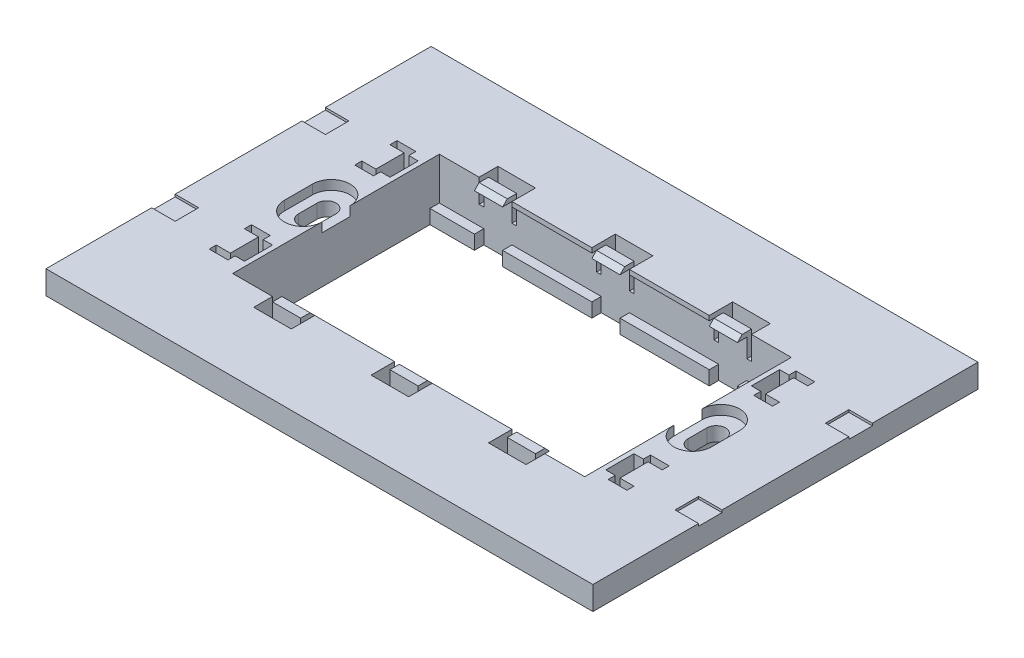
SolidWorks part; units mm, degrees
material "ABS"
ref_plane "Alzado" through (0, 0, 0) normal (0, 0, 1) x (1, 0, 0)
ref_plane "Planta" through (0, 0, 0) normal (0, 1, 0) x (1, 0, 0)
ref_plane "Vista lateral" through (0, 0, 0) normal (1, 0, 0) x (0, 0, -1)
sketch "Croquis1" plane through (0, 0, 0) normal (0, 1, 0) x (1, 0, 0)
  line L1 (-58.225, 41) -> (58.225, 41)
  line L2 (-58.225, 41) -> (-58.225, -41)
  line L3 (-58.225, -41) -> (58.225, -41)
  line L4 (58.225, 41) -> (58.225, -41)
  line L5 (-58.225, 41) -> (58.225, -41) construction
  line L6 (-58.225, -41) -> (58.225, 41) construction
  point P0 (0, 0)
  dimension "D1" = 82
  dimension "D2" = 116.45
extrude "Saliente-Extruir2" add sketch "Croquis1" along normal blind 5
sketch "Croquis2" plane through (0, 5, 0) normal (0, 1, 0) x (1, 0, 0)
  line L1 (-37.475, -22) -> (37.475, -22)
  line L2 (-37.475, -22) -> (-37.475, 22)
  line L3 (-37.475, 22) -> (37.475, 22)
  line L4 (37.475, -22) -> (37.475, 22)
  line L5 (-37.475, -22) -> (37.475, 22) construction
  line L6 (-37.475, 22) -> (37.475, -22) construction
  point P0 (0, 0)
  dimension "D1" = 74.95
  dimension "D2" = 44
extrude "Cortar-Extruir1" cut sketch "Croquis2" against normal blind 5
sketch "Croquis3" plane through (0, 0, 0) normal (0, -1, 0) x (1, 0, 0)
  line L1 (37.475, 22) -> (-37.475, 22)
  line L2 (37.475, 22) -> (37.475, -22)
  line L3 (37.475, -22) -> (-37.475, -22)
  line L4 (-37.475, 22) -> (-37.475, -22)
  line L5 (37.475, 22) -> (-37.475, -22) construction
  line L6 (37.475, -22) -> (-37.475, 22) construction
  line L7 (-38.475, 23) -> (38.475, 23)
  line L8 (-38.475, 23) -> (-38.475, -23)
  line L9 (-38.475, -23) -> (38.475, -23)
  line L10 (38.475, 23) -> (38.475, -23)
  line L11 (-38.475, 23) -> (38.475, -23) construction
  line L12 (-38.475, -23) -> (38.475, 23) construction
  point P0 (0, 0)
  point P7 (0, 0)
  dimension "D1" = 1
  dimension "D2" = 1
extrude "Saliente-Extruir3" add sketch "Croquis3" along normal blind 7
sketch "Croquis4" plane through (0, -7, 0) normal (0, -1, 0) x (1, 0, 0)
  line L0 (37.475, -22) -> (37.475, 22) construction
  line L1 (-37.475, 22) -> (37.475, 22)
  line L2 (-37.475, 22) -> (-37.475, 19)
  line L3 (-37.475, 19) -> (37.475, 19)
  line L4 (37.475, 22) -> (37.475, 19)
  line L5 (0, 0) -> (-23.0927, 0)
  line L6 (37.475, -22) -> (37.475, -19)
  line L7 (-37.475, -19) -> (37.475, -19)
  line L8 (-37.475, -22) -> (-37.475, -19)
  line L9 (-37.475, -22) -> (37.475, -22)
  line M5 (37.475, -22) -> (-37.475, -22)
  line M6 (-37.475, -22) -> (-37.475, 22)
  line M7 (-37.475, 22) -> (37.475, 22)
  line M8 (37.475, 22) -> (37.475, -22)
  dimension "D1" = 3
extrude "Saliente-Extruir4" add sketch "Croquis4" against normal blind 3 contours L3 M6 M8 M7 | L7 M6 M5 M8
sketch "Croquis5" plane through (0, -7, 0) normal (0, -1, 0) x (1, 0, 0)
  line L0 (0, -19) -> (0, -21)
  line L1 (-37.475, -19) -> (37.475, -19) construction
  line L2 (-3, -19) -> (-3, -21)
  line L3 (3, -19) -> (3, -21)
  line L4 (-3, -21) -> (3, -21)
  line L5 (-3, -19) -> (3, -19)
  line L6 (-25, -19) -> (-25, -13.1043)
  line L7 (-28, -19) -> (-28, -21)
  line L8 (-28, -21) -> (-22, -21)
  line L9 (-22, -21) -> (-22, -19)
  line L10 (-22, -19) -> (-28, -19)
  line L11 (0, 0) -> (-20.2994, 0)
  line L12 (-3, 19) -> (3, 19)
  line L13 (-3, 21) -> (3, 21)
  line L14 (3, 19) -> (3, 21)
  line L15 (-3, 19) -> (-3, 21)
  line L16 (0, 19) -> (0, 21)
  line L17 (-22, 19) -> (-28, 19)
  line L18 (-22, 21) -> (-22, 19)
  line L19 (-28, 21) -> (-22, 21)
  line L20 (-28, 19) -> (-28, 21)
  line L21 (-25, 19) -> (-25, 13.1043)
  line L22 (25, 19) -> (25, 13.1043)
  line L23 (28, 19) -> (28, 21)
  line L24 (28, 21) -> (22, 21)
  line L25 (22, 21) -> (22, 19)
  line L26 (22, 19) -> (28, 19)
  line L27 (22, -19) -> (28, -19)
  line L28 (22, -21) -> (22, -19)
  line L29 (28, -21) -> (22, -21)
  line L30 (28, -19) -> (28, -21)
  line L31 (25, -19) -> (25, -13.1043)
  line M2 (37.475, -19) -> (-37.475, -19)
  line M4 (-37.475, 19) -> (37.475, 19)
  dimension "D1" = 3
  dimension "D2" = 3
  dimension "D3" = 2
  dimension "D4" = 25
  dimension "D5" = 3
  dimension "D6" = 6
extrude "Cortar-Extruir9" cut sketch "Croquis5" against normal blind 3 contours L30 L27 L28 L29 M2 | L24 L25 L23 M4 | L16 L12 L14 L13 | L16 L13 L15 M4 | L2 L4 L0 M2 | L0 L4 L3 M2 | L8 L9 L7 M2 | L20 L17 L18 L19 M4
sketch "Croquis9" plane through (0, 0, 21) normal (0, 0, -1) x (-1, 0, 0)
  line L1 (28, -7) -> (22, -7)
  line L2 (28, -7) -> (28, -4)
  line L3 (28, -4) -> (22, -4)
  line L4 (22, -7) -> (22, -4)
  line L5 (-3, -4) -> (3, -4)
  line L6 (-3, -4) -> (-3, -7)
  line L7 (-3, -7) -> (3, -7)
  line L8 (3, -4) -> (3, -7)
  line L9 (-22, -4) -> (-28, -4)
  line L10 (-22, -4) -> (-22, -7)
  line L11 (-22, -7) -> (-28, -7)
  line L12 (-28, -4) -> (-28, -7)
extrude "Cortar-Extruir10" cut sketch "Croquis9" against normal blind 1
sketch "Croquis10" plane through (0, 0, 19) normal (0, 0, -1) x (-1, 0, 0)
  line L1 (37.475, -7) -> (-37.475, -7)
  line L2 (37.475, -7) -> (37.475, -4)
  line L3 (37.475, -4) -> (-37.475, -4)
  line L4 (-37.475, -7) -> (-37.475, -4)
extrude "Cortar-Extruir11" cut sketch "Croquis10" against normal blind 1
sketch "Croquis11" plane through (0, 0, -21) normal (0, 0, 1) x (1, 0, 0)
  line L0 (-3, -7) -> (3, -7) construction
  line L1 (28, -7) -> (22, -7)
  line L2 (28, -7) -> (28, -4)
  line L3 (28, -4) -> (22, -4)
  line L4 (22, -7) -> (22, -4)
  line L5 (-3, -4) -> (3, -4)
  line L6 (-3, -4) -> (-3, -7)
  line L7 (-3, -7) -> (3, -7)
  line L8 (3, -4) -> (3, -7)
  line L10 (-22, -7) -> (-28, -7)
  line L11 (-22, -7) -> (-22, -4)
  line L12 (-22, -4) -> (-28, -4)
  line L13 (-28, -7) -> (-28, -4)
extrude "Cortar-Extruir12" cut sketch "Croquis11" against normal blind 1
sketch "Croquis12" plane through (0, 0, -19) normal (0, 0, 1) x (1, 0, 0)
  line L1 (37.475, -7) -> (-37.475, -7)
  line L2 (37.475, -7) -> (37.475, -4)
  line L3 (37.475, -4) -> (-37.475, -4)
  line L4 (-37.475, -7) -> (-37.475, -4)
extrude "Cortar-Extruir13" cut sketch "Croquis12" against normal blind 1
sketch "Croquis13" plane through (0, 0, -22) normal (0, 0, 1) x (1, 0, 0)
  line L0 (-21, 0) -> (-22, 0)
  line L2 (37.475, 5) -> (-37.475, 5) construction
  line L3 (-22, 0) -> (-22, 5)
  line L4 (-21, 5) -> (-21, 0)
  line L5 (-21, 5) -> (-22, 5)
  line L6 (-25, -7) -> (-25, 5)
  line L7 (-28, -7) -> (-22, -7) construction
  line L8 (-29, 5) -> (-28, 5)
  line L9 (-29, 5) -> (-29, 0)
  line L10 (-28, 0) -> (-28, 5)
  line L11 (-29, 0) -> (-28, 0)
  line L12 (4, 5) -> (3, 5)
  line L13 (-4, 0) -> (-3, 0)
  line L14 (4, 5) -> (4, 0)
  line L15 (-3, 0) -> (-3, 5)
  line L16 (-4, 5) -> (-4, 0)
  line L17 (3, 0) -> (3, 5)
  line L18 (0, -7) -> (0, 5)
  line L19 (4, 0) -> (3, 0)
  line L20 (-4, 5) -> (-3, 5)
  line L21 (29, 5) -> (28, 5)
  line L22 (21, 0) -> (22, 0)
  line L23 (29, 5) -> (29, 0)
  line L24 (22, 0) -> (22, 5)
  line L25 (21, 5) -> (21, 0)
  line L26 (28, 0) -> (28, 5)
  line L27 (25, -7) -> (25, 5)
  line L28 (29, 0) -> (28, 0)
  line L29 (21, 5) -> (22, 5)
  line M3 (37.475, 5) -> (-37.475, 5)
  dimension "D1" = 1
  dimension "D2" = 1
  dimension "D3" = 1
extrude "Cortar-Extruir21" cut sketch "Croquis13" against normal blind 4 contours L25 L22 L24 M3 | L19 L14 L17 M3 | L16 L13 L15 M3 | L9 L11 L10 M3 | L4 L3 L0 M3 | L23 L28 L26 L21
sketch "Croquis14" plane through (0, 0, 22) normal (0, 0, -1) x (-1, 0, 0)
  line L0 (25, -7) -> (25, 5)
  line L1 (22, -7) -> (28, -7) construction
  line L2 (37.475, 5) -> (-37.475, 5) construction
  line L3 (29, 5) -> (29, 0)
  line L4 (28, 0) -> (28, 5)
  line L5 (29, 0) -> (28, 0)
  line L6 (29, 5) -> (28, 5)
  line L7 (21, 5) -> (22, 5)
  line L8 (21, 0) -> (22, 0)
  line L9 (22, 0) -> (22, 5)
  line L10 (21, 5) -> (21, 0)
  line L11 (-4, 5) -> (-3, 5)
  line L12 (-4, 0) -> (-3, 0)
  line L13 (-3, 0) -> (-3, 5)
  line L14 (4, 5) -> (4, 0)
  line L15 (3, 0) -> (3, 5)
  line L16 (-4, 5) -> (-4, 0)
  line L17 (4, 0) -> (3, 0)
  line L18 (4, 5) -> (3, 5)
  line L19 (-29, 5) -> (-28, 5)
  line L20 (-29, 0) -> (-28, 0)
  line L21 (-28, 0) -> (-28, 5)
  line L22 (-21, 5) -> (-21, 0)
  line L23 (-22, 0) -> (-22, 5)
  line L24 (-29, 5) -> (-29, 0)
  line L25 (-21, 0) -> (-22, 0)
  line L26 (-21, 5) -> (-22, 5)
  line M3 (37.475, 5) -> (-37.475, 5)
  dimension "D1" = 1
  dimension "D2" = 5
  dimension "D3" = 1
  dimension "D4" = 5
  dimension "D5" = 1
  dimension "D6" = 5
extrude "Cortar-Extruir22" cut sketch "Croquis14" against normal blind 4 contours L5 L3 L4 M3 | L25 L22 L23 M3 | L10 L8 L9 L7 | L14 L17 L15 L18 | L16 L12 L13 L11 | L24 L20 L21 L19
sketch "Croquis15" plane through (0, 0, 0) normal (0, -1, 0) x (1, 0, 0)
  line L0 (-4, 23) -> (4, 23)
  line L1 (-29, 26) -> (-21, 26)
  line L2 (-29, 26) -> (-29, 23)
  line L3 (-29, 23) -> (-21, 23)
  line L4 (-21, 26) -> (-21, 23)
  line L5 (4, 26) -> (4, 23)
  line L6 (-4, 26) -> (-4, 23)
  line L7 (-4, 26) -> (4, 26)
  line L8 (21, 23) -> (29, 23)
  line L9 (29, 26) -> (29, 23)
  line L10 (21, 26) -> (21, 23)
  line L11 (21, 26) -> (29, 26)
  line L12 (-29, -26) -> (-21, -26)
  line L13 (-21, -23) -> (-21, -26)
  line L14 (-29, -23) -> (-29, -26)
  line L15 (-29, -23) -> (-21, -23)
  line L16 (-4, -26) -> (4, -26)
  line L17 (4, -23) -> (4, -26)
  line L18 (-4, -23) -> (-4, -26)
  line L19 (-4, -23) -> (4, -23)
  line L20 (21, -26) -> (29, -26)
  line L21 (29, -23) -> (29, -26)
  line L22 (21, -23) -> (21, -26)
  line L23 (21, -23) -> (29, -23)
extrude "Cortar-Extruir23" cut sketch "Croquis15" against normal blind 16
sketch "Croquis16" plane through (37.475, 0, 0) normal (-1, 0, 0) x (0, 0, 1)
  line L0 (-22, 5) -> (-21, 5)
  line L1 (22, 5) -> (-22, 5) construction
  line L2 (-20, 4) -> (-22, 4)
  line L3 (-22, -4) -> (-22, 5) construction
  line L4 (-20, 4) -> (-21, 5)
  line L5 (-22, 4) -> (-22, 5)
extrude "Saliente-Extruir8" add sketch "Croquis16" along normal blind 70
sketch "Croquis17" plane through (37.475, 0, 0) normal (-1, 0, 0) x (0, 0, 1)
  line L0 (22, 5) -> (12, 5)
  line L1 (22, 5) -> (-21, 5) construction
  line L2 (22, 5) -> (21, 5)
  line L3 (22, 5) -> (22, 4)
  line L4 (21, 4) -> (22, 4)
  line L5 (22, -4) -> (22, 5) construction
  line L6 (22, 4) -> (20, 4)
  line L7 (20, 4) -> (21, 5)
  line M8 (22, -4) -> (22, 5)
  line M9 (22, 5) -> (-21, 5)
extrude "Saliente-Extruir9" add sketch "Croquis17" along normal blind 70 contours L7 L6 L4 M8 M9
sketch "Croquis18" plane through (0, 5, 0) normal (0, 1, 0) x (1, 0, 0)
  line L0 (-22, 22) -> (-22, 21)
  line L1 (-32.525, 21) -> (37.475, 21) construction
  line L2 (-3, -22) -> (-3, -21)
  line L3 (-32.525, -21) -> (37.475, -21) construction
  line L4 (22, -21) -> (22, 21)
  line L5 (-3, -21) -> (-22, -21)
  line L6 (-3, -21) -> (-3, 21)
  line L7 (-3, 21) -> (-22, 21)
  line L8 (-22, -21) -> (-22, 21)
  line L9 (22, -21) -> (3, -21)
  line L10 (3, -21) -> (3, 21)
  line L11 (22, 21) -> (3, 21)
extrude "Cortar-Extruir24" cut sketch "Croquis18" against normal blind 8 contours L8 L5 L6 L7 | L4 L11 L10 L9
sketch "Croquis19" plane through (0, 5, 0) normal (0, 1, 0) x (1, 0, 0)
  line L0 (37.475, 22) -> (28, 22)
  line L1 (-28, 22) -> (-37.475, 22)
  line L2 (-28, 22) -> (-28, -22)
  line L3 (-28, -22) -> (-37.475, -22)
  line L4 (-37.475, 22) -> (-37.475, -22)
  line L5 (37.475, -22) -> (28, -22)
  line L6 (28, 22) -> (28, -22)
  line L7 (37.475, 22) -> (37.475, -22)
extrude "Cortar-Extruir26" cut sketch "Croquis19" against normal blind 8
sketch "Croquis20" plane through (0, 5, 0) normal (0, 1, 0) x (1, 0, 0)
  line L0 (-4, -22) -> (-3, -22)
  line L1 (-22, 22) -> (-21, 22)
  line L2 (-22, 22) -> (-22, -22)
  line L3 (-22, -22) -> (-21, -22)
  line L4 (-21, 22) -> (-21, -22)
  line L5 (-3, 22) -> (-3, -22)
  line L6 (-4, 22) -> (-4, -22)
  line L7 (-4, 22) -> (-3, 22)
  line L8 (3, -22) -> (4, -22)
  line L9 (4, 22) -> (4, -22)
  line L10 (3, 22) -> (3, -22)
  line L11 (3, 22) -> (4, 22)
  line L12 (21, -22) -> (22, -22)
  line L13 (22, 22) -> (22, -22)
  line L14 (21, 22) -> (21, -22)
  line L15 (21, 22) -> (22, 22)
extrude "Cortar-Extruir27" cut sketch "Croquis20" against normal blind 4
sketch "Croquis21" plane through (0, 5, 0) normal (0, 1, 0) x (1, 0, 0)
  line L0 (-58.225, 41) -> (-58.225, -41) construction
  line L1 (-58.225, 18.5) -> (-53.225, 18.5)
  line L2 (-58.225, 18.5) -> (-58.225, 13.5)
  line L3 (-58.225, 13.5) -> (-53.225, 13.5)
  line L4 (-53.225, 18.5) -> (-53.225, 13.5)
  line L5 (-37.475, 22) -> (-37.475, -22) construction
  line L6 (-53.225, 16) -> (-43.6218, 16)
  line L7 (0, 0) -> (0, -10.1359)
  line L8 (0, 0) -> (-11.9942, 0)
  line L9 (-53.225, -16) -> (-43.6218, -16)
  line L10 (-53.225, -18.5) -> (-53.225, -13.5)
  line L11 (-58.225, -13.5) -> (-53.225, -13.5)
  line L12 (-58.225, -18.5) -> (-58.225, -13.5)
  line L13 (-58.225, -18.5) -> (-53.225, -18.5)
  line L14 (53.225, -16) -> (43.6218, -16)
  line L15 (58.225, -18.5) -> (53.225, -18.5)
  line L16 (53.225, -18.5) -> (53.225, -13.5)
  line L17 (53.225, 18.5) -> (53.225, 13.5)
  line L18 (58.225, 13.5) -> (53.225, 13.5)
  line L19 (58.225, 18.5) -> (58.225, 13.5)
  line L20 (58.225, 18.5) -> (53.225, 18.5)
  line L21 (58.225, -18.5) -> (58.225, -13.5)
  line L22 (58.225, -13.5) -> (53.225, -13.5)
  line L23 (53.225, 16) -> (43.6218, 16)
  point P11 (-37.475, 0)
  line M29 (58.225, -41) -> (58.225, 41)
  line M31 (-58.225, 41) -> (-58.225, -41)
  dimension "D1" = 5
  dimension "D2" = 5
  dimension "D3" = 16
extrude "Cortar-Extruir28" cut sketch "Croquis21" against normal blind 0.5 contours L13 L10 L11 M31 | L4 L1 L3 M31 | L22 L16 L15 M29 | L19 L18 L17 L20
sketch "Croquis22" plane through (0, 5, 0) normal (0, 1, 0) x (1, 0, 0)
  line L0 (-37.475, 0) -> (-39.475, 0)
  line L1 (-37.475, 22) -> (-37.475, -22) construction
  line L2 (-39.475, -2) -> (-39.475, 2)
  line L3 (-43.475, 2) -> (-43.475, -2)
  line L4 (0, 0) -> (0, -8.6963)
  line L5 (43.475, 2) -> (43.475, -2)
  line L6 (39.475, -2) -> (39.475, 2)
  line L7 (37.475, 0) -> (39.475, 0)
  arc A0 (-43.475, -2) -> (-39.475, -2) centre (-41.475, -2) ccw
  arc A1 (-39.475, 2) -> (-43.475, 2) centre (-41.475, 2) ccw
  arc A2 (39.475, 2) -> (43.475, 2) centre (41.475, 2) cw
  arc A3 (43.475, -2) -> (39.475, -2) centre (41.475, -2) cw
  dimension "D1" = 2
  dimension "D2" = 4
  dimension "D3" = 2
  dimension "D4" = 4
extrude "Cortar-Extruir29" cut sketch "Croquis22" against normal blind 5 contours L2 A1 L3 A0 | A3 L5 A2 L6
sketch "Croquis23" plane through (0, 5, 0) normal (0, 1, 0) x (1, 0, 0)
  line L0 (0, 0) -> (0, 7.9914)
  line L1 (-37.475, 22) -> (-37.475, -22) construction
  line L2 (-37.475, 0) -> (-37.475, -3)
  line L3 (-37.475, 0) -> (-37.475, 3)
  line L4 (-45.475, 3) -> (-45.475, -3)
  line L5 (45.475, 3) -> (45.475, -3)
  line L6 (37.475, 0) -> (37.475, 3)
  line L7 (37.475, 0) -> (37.475, -3)
  arc A0 (-45.475, -3) -> (-37.475, -3) centre (-41.475, -3) ccw
  arc A1 (-37.475, 3) -> (-45.475, 3) centre (-41.475, 3) ccw
  arc A2 (37.475, 3) -> (45.475, 3) centre (41.475, 3) cw
  arc A3 (45.475, -3) -> (37.475, -3) centre (41.475, -3) cw
extrude "Cortar-Extruir30" cut sketch "Croquis23" against normal blind 2 contours L3 A1 L4 A0 L2 | A3 L5 A2 L6 L7
sketch "Croquis24" plane through (0, 5, 0) normal (0, 1, 0) x (1, 0, 0)
  line L3 (-38.475, -12.5) -> (-38.475, -18.5)
  line L4 (-38.475, -18.5) -> (-40.475, -18.5)
  line L5 (-40.475, -18.5) -> (-40.475, -20)
  line L6 (-40.475, -20) -> (-44.475, -20)
  line L7 (-44.475, -20) -> (-44.475, -18.5)
  line L8 (-44.475, -18.5) -> (-41.475, -18.5)
  line L9 (-41.475, -18.5) -> (-41.475, -12.5)
  line L13 (-44.475, -12.5) -> (-41.475, -12.5)
  line L14 (-44.475, -11) -> (-44.475, -12.5)
  line L15 (-40.475, -11) -> (-44.475, -11)
  line L16 (-40.475, -12.5) -> (-40.475, -11)
  line L17 (-38.475, -12.5) -> (-40.475, -12.5)
  line L18 (-38.475, 12.5) -> (-40.475, 12.5)
  line L19 (-40.475, 12.5) -> (-40.475, 11)
  line L20 (-40.475, 11) -> (-44.475, 11)
  line L21 (-44.475, 11) -> (-44.475, 12.5)
  line L22 (-44.475, 12.5) -> (-41.475, 12.5)
  line L24 (-41.475, 18.5) -> (-41.475, 12.5)
  line L25 (-44.475, 18.5) -> (-41.475, 18.5)
  line L26 (-44.475, 20) -> (-44.475, 18.5)
  line L27 (-40.475, 20) -> (-44.475, 20)
  line L28 (-40.475, 18.5) -> (-40.475, 20)
  line L29 (-38.475, 18.5) -> (-40.475, 18.5)
  line L30 (-38.475, 12.5) -> (-38.475, 18.5)
  line L35 (38.475, 12.5) -> (38.475, 18.5)
  line L36 (38.475, 18.5) -> (40.475, 18.5)
  line L37 (40.475, 18.5) -> (40.475, 20)
  line L38 (40.475, 20) -> (44.475, 20)
  line L39 (44.475, 20) -> (44.475, 18.5)
  line L40 (44.475, 18.5) -> (41.475, 18.5)
  line L41 (41.475, 18.5) -> (41.475, 12.5)
  line L43 (44.475, 12.5) -> (41.475, 12.5)
  line L44 (44.475, 11) -> (44.475, 12.5)
  line L45 (40.475, 11) -> (44.475, 11)
  line L46 (40.475, 12.5) -> (40.475, 11)
  line L47 (38.475, 12.5) -> (40.475, 12.5)
  line L48 (38.475, -12.5) -> (40.475, -12.5)
  line L49 (40.475, -12.5) -> (40.475, -11)
  line L50 (40.475, -11) -> (44.475, -11)
  line L51 (44.475, -11) -> (44.475, -12.5)
  line L52 (44.475, -12.5) -> (41.475, -12.5)
  line L53 (41.475, -18.5) -> (41.475, -12.5)
  line L55 (44.475, -18.5) -> (41.475, -18.5)
  line L56 (44.475, -20) -> (44.475, -18.5)
  line L57 (40.475, -20) -> (44.475, -20)
  line L58 (40.475, -18.5) -> (40.475, -20)
  line L59 (38.475, -18.5) -> (40.475, -18.5)
  line L60 (38.475, -12.5) -> (38.475, -18.5)
  point P19 (-41.475, -15.5)
  point P42 (-41.475, 15.5)
  point P77 (41.475, 15.5)
  point P78 (41.475, -15.5)
  dimension "D2" = 2
  dimension "D3" = 1.5
extrude "Cortar-Extruir31" cut sketch "Croquis24" against normal blind 5
